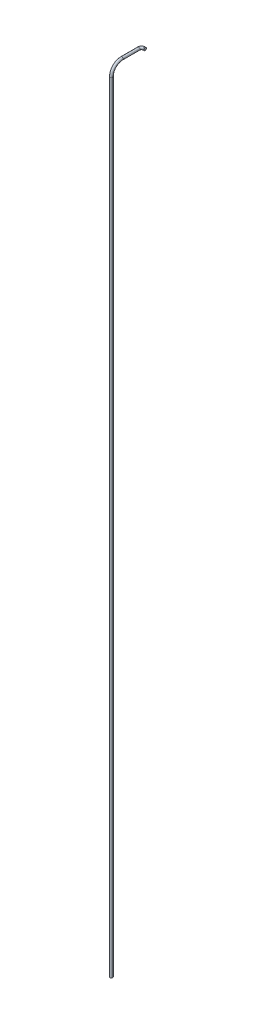
SolidWorks part; units mm, degrees
material "PVC Rígido"
ref_plane "Plano frontal" through (0, 0, 0) normal (0, 0, 1) x (1, 0, 0)
ref_plane "Plano superior" through (0, 0, 0) normal (0, 1, 0) x (1, 0, 0)
ref_plane "Plano direito" through (0, 0, 0) normal (1, 0, 0) x (0, 0, -1)
sketch "Esboço1" plane through (0, 0, 0) normal (1, 0, 0) x (0, 0, -1)
  line L0 (0, 0) -> (-30, 0)
  line L1 (-50, -20) -> (-50, -1500)
  arc A1 (-30, 0) -> (-50, -20) centre (-30, -20) ccw
  point P7 (-50, -1505)
  point P10 (-50, 0)
  point P11 (-50, -1520)
  dimension "D2" = 20
  dimension "D1" = 50
  dimension "D3" = 1500
sweep "Varredura1" add path "Esboço1" circular profile diameter 5 parameters "D3"=5
sketch "Esboço22" plane through (0, 0, 0) normal (0, 1, 0) x (1, 0, 0)
  line L0 (0, 0) -> (0, 2)
  line L1 (5, 7) -> (6.9966, 7)
  arc A0 (0, 2) -> (5, 7) centre (5, 2) cw
  dimension "D1" = 5
  dimension "D2" = 2
sweep "Varredura2" add path "Esboço22" circular profile diameter 5 parameters "D3"=5
ref_plane "Plano1" through (0, -1500, 0) normal (0, -1, 0) x (-1, 0, 0)
